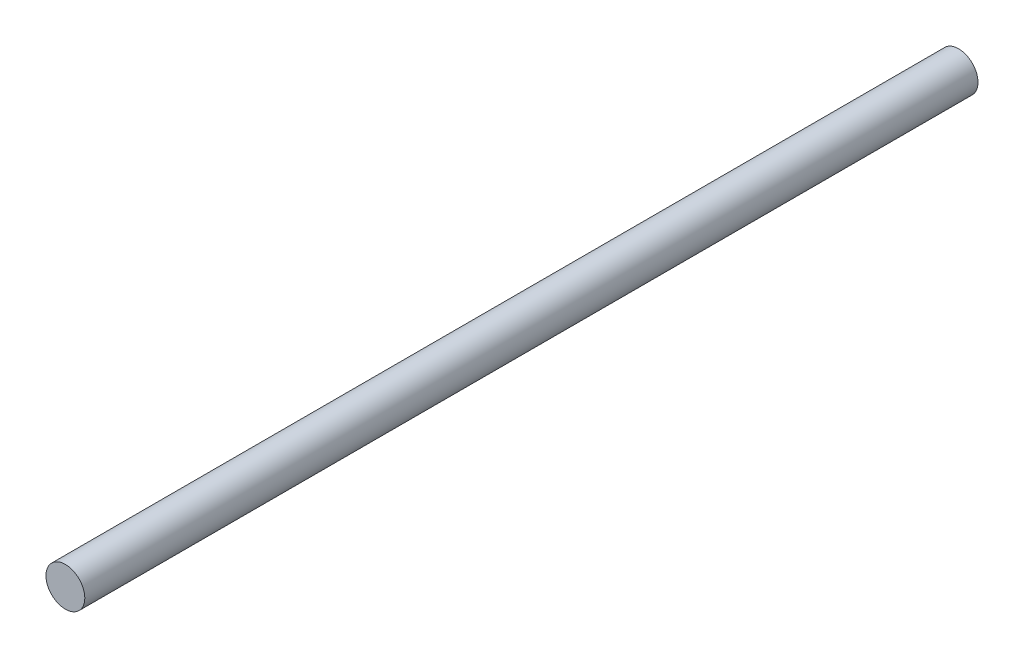
SolidWorks part; units mm, degrees
material "AISI 1020 Steel, Cold Rolled"
ref_plane "Płaszczyzna przednia" through (0, 0, 0) normal (0, 0, 1) x (1, 0, 0)
ref_plane "Płaszczyzna górna" through (0, 0, 0) normal (0, 1, 0) x (1, 0, 0)
ref_plane "Płaszczyzna prawa" through (0, 0, 0) normal (1, 0, 0) x (0, 0, -1)
sketch "Szkic1" plane through (0, 0, 0) normal (0, 0, 1) x (1, 0, 0)
  circle A0 centre (0, 0) radius 5
  dimension "D1" = 10
extrude "Dodanie-wyciągnięcie1" add sketch "Szkic1" along normal blind 230
